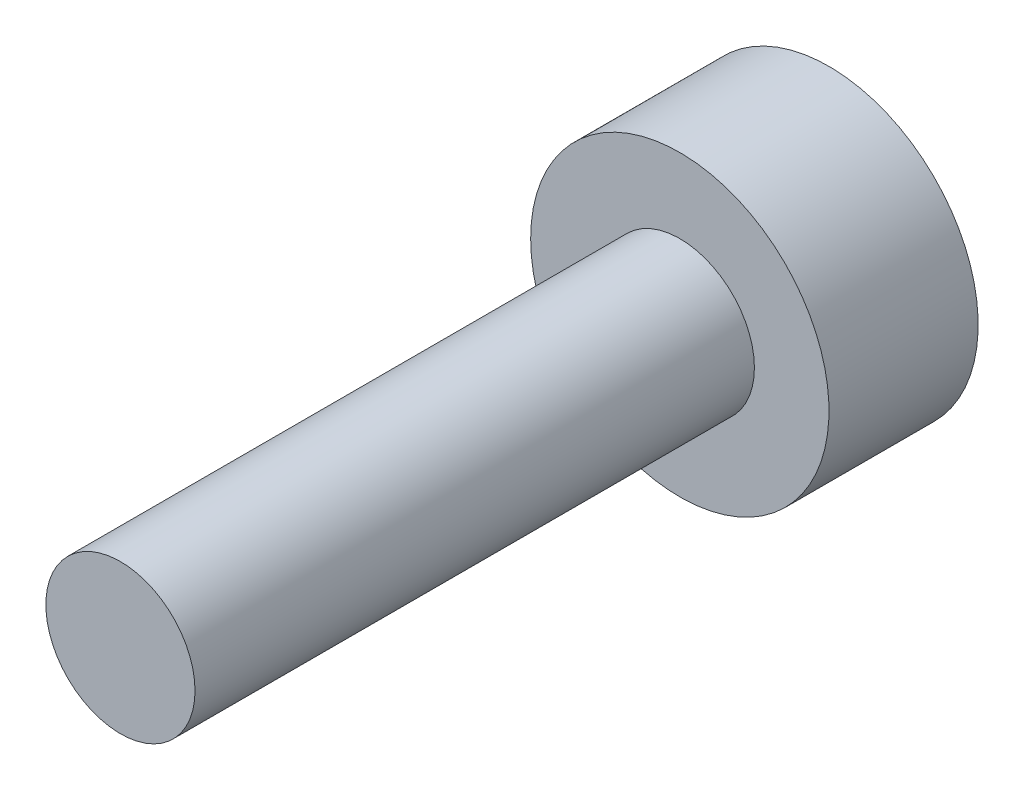
SolidWorks part; units mm, degrees
ref_plane "前视基准面" through (0, 0, 0) normal (0, 0, 1) x (1, 0, 0)
ref_plane "上视基准面" through (0, 0, 0) normal (0, 1, 0) x (1, 0, 0)
ref_plane "右视基准面" through (0, 0, 0) normal (1, 0, 0) x (0, 0, -1)
sketch "草图1" plane through (0, 0, 0) normal (0, 0, 1) x (1, 0, 0)
  circle A0 centre (0, 0) radius 0.8
extrude "凸台-拉伸1" add sketch "草图1" along normal blind 6
sketch "草图2" plane through (0, 0, 0) normal (0, 0, -1) x (-1, 0, 0)
  circle A0 centre (0, 0) radius 1.6
extrude "凸台-拉伸2" add sketch "草图2" along normal blind 1.6
sketch "草图3" plane through (0, 0, -1.6) normal (0, 0, -1) x (-1, 0, 0)
  line L1 (0.8, 0) -> (0.4, 0.6928)
  line L2 (0.4, 0.6928) -> (-0.4, 0.6928)
  line L3 (-0.4, 0.6928) -> (-0.8, 0)
  line L4 (-0.8, 0) -> (-0.4, -0.6928)
  line L5 (-0.4, -0.6928) -> (0.4, -0.6928)
  line L6 (0.4, -0.6928) -> (0.8, 0)
  circle A1 centre (0, 0) radius 0.8 construction
extrude "切除-拉伸1" cut sketch "草图3" against normal blind 0.8
